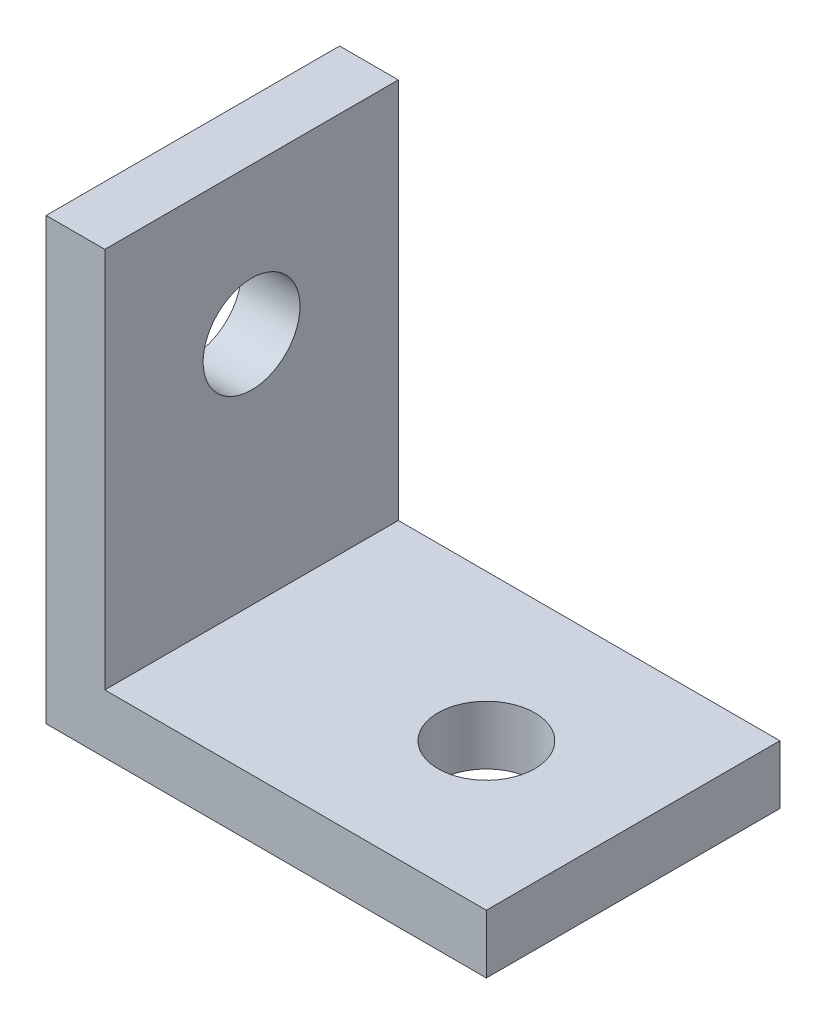
SolidWorks part; units mm, degrees
material "Alumina"
ref_plane "Plano frontal" through (0, 0, 0) normal (0, 0, 1) x (1, 0, 0)
ref_plane "Plano superior" through (0, 0, 0) normal (0, 1, 0) x (1, 0, 0)
ref_plane "Plano direito" through (0, 0, 0) normal (1, 0, 0) x (0, 0, -1)
sketch "Esboço1" plane through (0, 0, 0) normal (0, 0, 1) x (1, 0, 0)
  line L0 (0, 0) -> (15, 0)
  line L1 (15, 0) -> (15, 2)
  line L2 (15, 2) -> (2, 2)
  line L3 (2, 2) -> (2, 15)
  line L4 (2, 15) -> (0, 15)
  line L5 (0, 15) -> (0, 0)
  dimension "D1" = 15
  dimension "D2" = 15
  dimension "D3" = 2
  dimension "D4" = 2
extrude "Ressalto-extrusão2" add sketch "Esboço1" along normal blind 10
sketch "Esboço3" plane through (2, 0, 0) normal (1, 0, 0) x (0, 0, -1)
  line L0 (0, 2) -> (0, 15) construction
  line L1 (-10, 15) -> (0, 15) construction
  point P0 (-5, 10)
  dimension "D1" = 5
  dimension "D2" = 5
hole_wizard "Broca de rosquear para tarraxa de M4x0.72" positions "3DSketch1" profile "Esboço4" hole size "M4x0.7" standard "Ansi Metric" end condition through all
sketch3d "3DSketch1"
  point P0 (2, 10, 5)
sketch "Esboço4" plane through (2, 10, 5) normal (0, 1, 0) x (0, 0, -1)
  line L0 (0, 0) -> (0, 2)
  line L1 (0, 2) -> (1.65, 2)
  line L2 (1.65, 2) -> (1.65, 0)
  line L5 (1.65, 0) -> (0, 0)
  line L11 (0, -6.35) -> (0, 107.95) construction
  dimension "Thru Hole Dia." = 3.3
  dimension "Thru Hole Depth" = 2
sketch "Esboço5" plane through (0, 0, 0) normal (0, -1, 0) x (1, 0, 0)
  line L1 (15, 10) -> (2, 10) construction
  line L2 (15, 10) -> (15, 0) construction
  point P0 (10, 5)
  dimension "D1" = 5
  dimension "D2" = 5
hole_wizard "Broca de rosquear para tarraxa de M4x0.71" positions "3DSketch2" profile "Esboço6" hole size "M4x0.7" standard "Ansi Metric" end condition through all
sketch3d "3DSketch2"
  point P0 (10, 0, 5)
sketch "Esboço6" plane through (10, 0, 5) normal (1, 0, 0) x (0, 0, -1)
  line L0 (0, 0) -> (0, 15)
  line L1 (0, 15) -> (1.65, 15)
  line L2 (1.65, 15) -> (1.65, 0)
  line L5 (1.65, 0) -> (0, 0)
  line L11 (0, -6.35) -> (0, 107.95) construction
  dimension "Thru Hole Dia." = 3.3
  dimension "Thru Hole Depth" = 15
